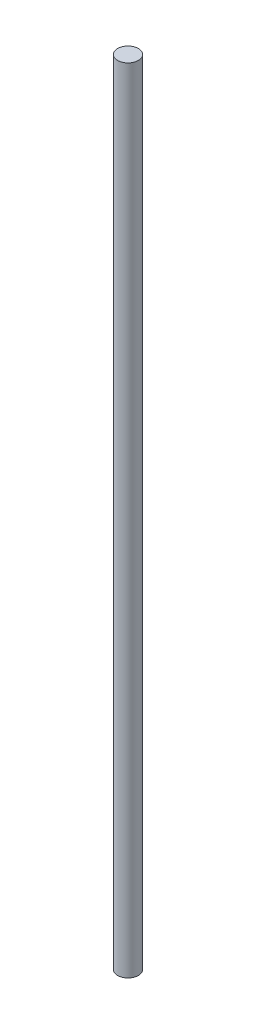
SolidWorks part; units mm, degrees
ref_plane "Front Plane" through (0, 0, 0) normal (0, 0, 1) x (1, 0, 0)
ref_plane "Top Plane" through (0, 0, 0) normal (0, 1, 0) x (1, 0, 0)
ref_plane "Right Plane" through (0, 0, 0) normal (1, 0, 0) x (0, 0, -1)
sketch "Sketch1" plane through (0, 0, 0) normal (0, 1, 0) x (1, 0, 0)
  circle A0 centre (0, 0) radius 3
extrude "Boss-Extrude1" add sketch "Sketch1" along normal blind 229.5
